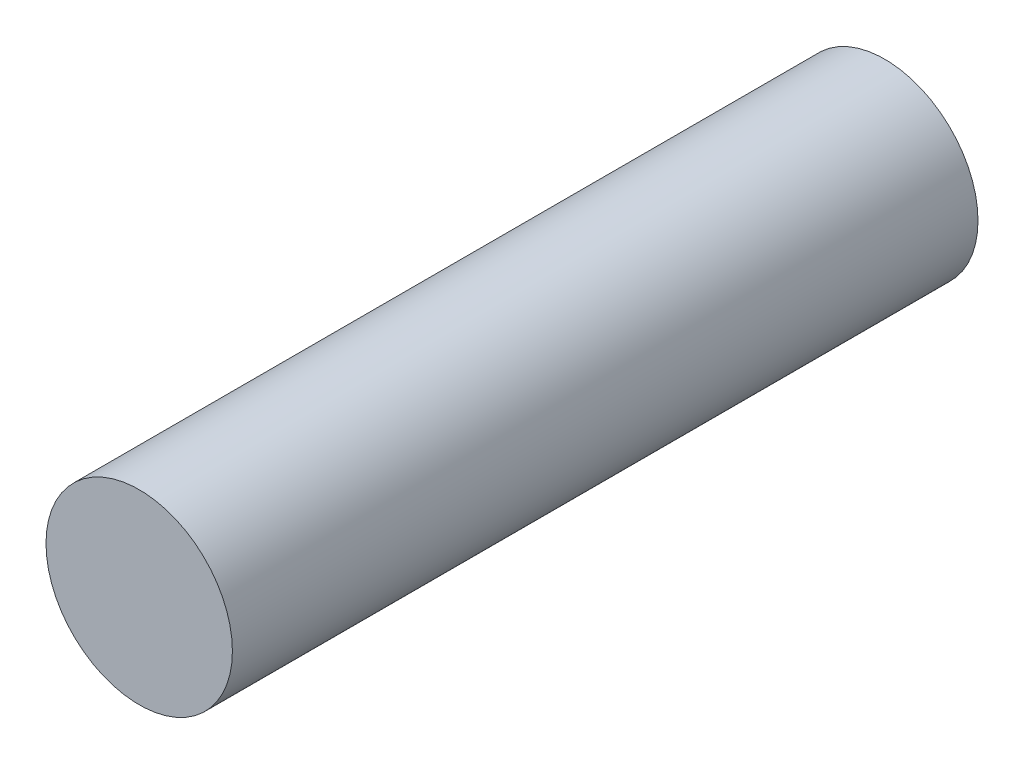
SolidWorks part; units mm, degrees
ref_plane "Front Plane" through (0, 0, 0) normal (0, 0, 1) x (1, 0, 0)
ref_plane "Top Plane" through (0, 0, 0) normal (0, 1, 0) x (1, 0, 0)
ref_plane "Right Plane" through (0, 0, 0) normal (1, 0, 0) x (0, 0, -1)
sketch "Sketch1" plane through (0, 0, 0) normal (0, 0, 1) x (1, 0, 0)
  circle A0 centre (0, 0) radius 50
  dimension "D1" = 100
extrude "Boss-Extrude1" add sketch "Sketch1" along normal mid plane 400
